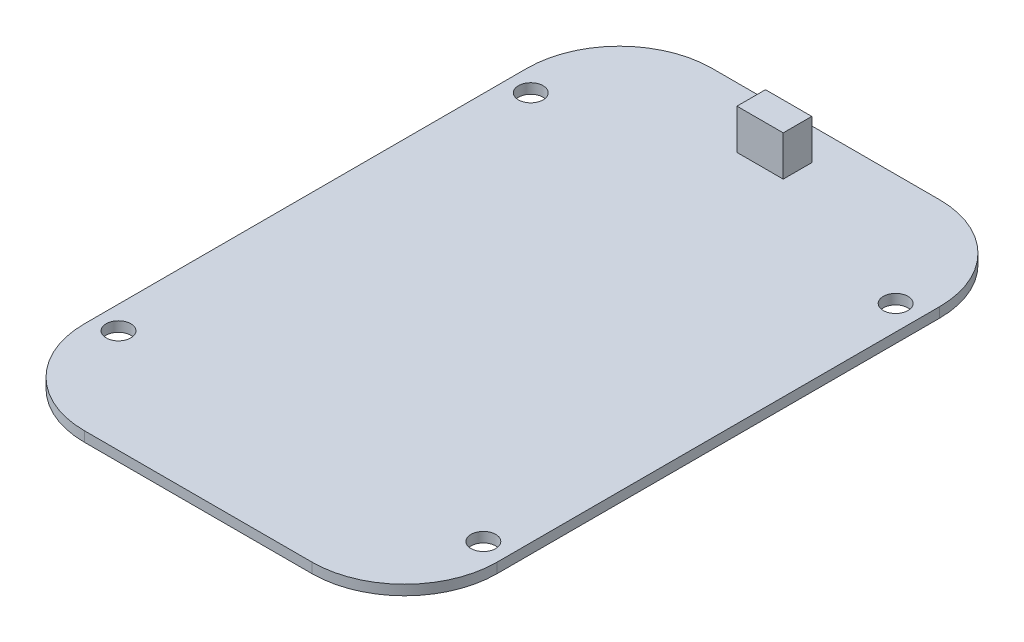
SolidWorks part; units mm, degrees
ref_plane "Front Plane" through (0, 0, 0) normal (0, 0, 1) x (1, 0, 0)
ref_plane "Top Plane" through (0, 0, 0) normal (0, 1, 0) x (1, 0, 0)
ref_plane "Right Plane" through (0, 0, 0) normal (1, 0, 0) x (0, 0, -1)
sketch "Sketch1" plane through (0, 0, 0) normal (0, 1, 0) x (1, 0, 0)
  line L1 (-20.8016, 33.7745) -> (8.7284, 33.7745)
  line L2 (-32.8016, 21.7745) -> (-32.8016, -35.6255)
  line L3 (-20.8016, -47.6255) -> (8.7284, -47.6255)
  line L4 (20.7284, 21.7745) -> (20.7284, -35.6255)
  arc A0 (-32.8016, -35.6255) -> (-20.8016, -47.6255) centre (-20.8016, -35.6255) ccw
  arc A1 (8.7284, -47.6255) -> (20.7284, -35.6255) centre (8.7284, -35.6255) ccw
  arc A2 (20.7284, 21.7745) -> (8.7284, 33.7745) centre (8.7284, 21.7745) ccw
  arc A3 (-32.8016, 21.7745) -> (-20.8016, 33.7745) centre (-20.8016, 21.7745) cw
  point P6 (-32.8016, -47.6255)
  point P11 (20.7284, 33.7745)
  point P14 (-32.8016, 33.7745)
  dimension "D3" = 12
  dimension "D1" = 53.53
  dimension "D2" = 81.4
extrude "Boss-Extrude1" add sketch "Sketch1" along normal blind 1.3
sketch "Sketch2" plane through (0, 1.3, 0) normal (0, 1, 0) x (1, 0, 0)
  line L0 (-32.8016, 21.7745) -> (-32.8016, -35.6255) construction
  line L1 (8.7284, 33.7745) -> (-20.8016, 33.7745) construction
  circle A0 centre (-29.8016, 19.2745) radius 1.6
  circle A1 centre (17.5184, 19.2745) radius 1.6
  circle A2 centre (17.5184, -34.1955) radius 1.6
  circle A3 centre (-29.8016, -34.1955) radius 1.6
  dimension "D1" = 3.2
  dimension "D2" = 3
  dimension "D3" = 14.5
  dimension "D4" = 2
  dimension "D5" = 2
extrude "Cut-Extrude1" cut sketch "Sketch2" against normal blind 1.3
sketch "Sketch3" plane through (0, 1.3, 0) normal (0, 1, 0) x (1, 0, 0)
  line L0 (-32.8016, 21.7745) -> (-32.8016, -35.6255) construction
  line L1 (-9.7316, 29.6445) -> (-3.7316, 29.6445)
  line L2 (-9.7316, 29.6445) -> (-9.7316, 25.9445)
  line L3 (-9.7316, 25.9445) -> (-3.7316, 25.9445)
  line L4 (-3.7316, 29.6445) -> (-3.7316, 25.9445)
  line L5 (8.7284, 33.7745) -> (-20.8016, 33.7745) construction
  dimension "D1" = 3.7
  dimension "D2" = 6
  dimension "D3" = 29.07
  dimension "D4" = 7.83
extrude "Boss-Extrude2" add sketch "Sketch3" along normal blind 5.2
